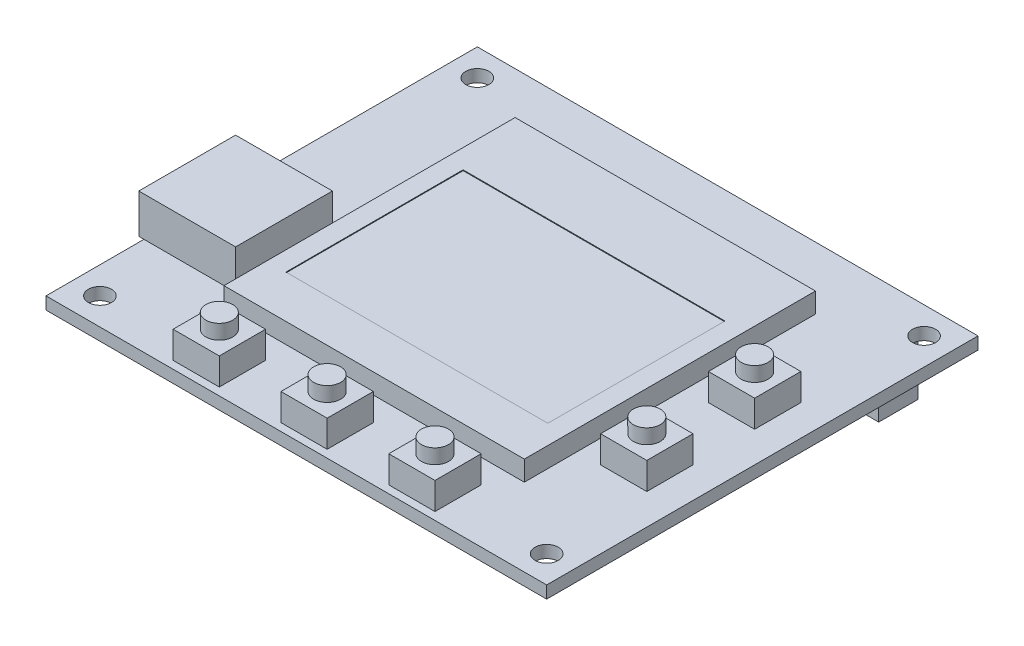
SolidWorks part; units mm, degrees
other "OLED"
other "PCB"
ref_plane "Front Plane" through (0, 0, 0) normal (0, 0, 1) x (1, 0, 0)
ref_plane "Top Plane" through (0, 0, 0) normal (0, 1, 0) x (1, 0, 0)
ref_plane "Right Plane" through (0, 0, 0) normal (1, 0, 0) x (0, 0, -1)
sketch "Sketch1" plane through (0, 0, 0) normal (0, 1, 0) x (1, 0, 0)
  line L1 (-32.5, -28) -> (32.5, -28)
  line L2 (-32.5, -28) -> (-32.5, 28)
  line L3 (-32.5, 28) -> (32.5, 28)
  line L4 (32.5, -28) -> (32.5, 28)
  line L5 (0, 28) -> (0, -28) construction
  line L6 (-32.5, 0) -> (32.5, 0) construction
  line L7 (-29, -24.5) -> (29, -24.5) construction
  line L8 (-29, -24.5) -> (-29, 24.5) construction
  line L9 (-29, 24.5) -> (29, 24.5) construction
  line L10 (29, -24.5) -> (29, 24.5) construction
  line L11 (0, 24.5) -> (0, -24.5) construction
  line L12 (-29, 0) -> (29, 0) construction
  circle A0 centre (-29, 24.5) radius 1.5
  circle A1 centre (29, 24.5) radius 1.5
  circle A2 centre (29, -24.5) radius 1.5
  circle A3 centre (-29, -24.5) radius 1.5
  point P0 (0, 0)
  point P4 (0, 0)
  dimension "D5" = 3
  dimension "D1" = 65
  dimension "D2" = 56
  dimension "D3" = 49
  dimension "D4" = 58
extrude "Boss-Extrude1" add sketch "Sketch1" along normal blind 1.6
sketch "Sketch2" plane through (0, 1.6, 0) normal (0, 1, 0) x (1, 0, 0)
  line L0 (-32.5, -28) -> (-32.5, 28) construction
  line L1 (-19.5, -17.9) -> (19.5, -17.9)
  line L2 (-19.5, -17.9) -> (-19.5, 19.9)
  line L3 (-19.5, 19.9) -> (19.5, 19.9)
  line L4 (19.5, -17.9) -> (19.5, 19.9)
  line L5 (0, 19.9) -> (0, -17.9) construction
  line L6 (-19.5, 1) -> (19.5, 1) construction
  line L7 (-32.5, -28) -> (32.5, -28) construction
  point P0 (0, 1)
  dimension "D1" = 32.5
  dimension "D2" = 39
  dimension "D3" = 37.8
  dimension "D4" = 29
  dimension "D5" = 10.1
extrude "Boss-Extrude2" add sketch "Sketch2" along normal blind 2.6 separate body
sketch "Sketch3" plane through (0, 4.2, 0) normal (0, 1, 0) x (1, 0, 0)
  line L0 (0, 19.9) -> (0, -17.9) construction
  line L1 (-17, 10.65) -> (17, 10.65)
  line L2 (-17, 10.65) -> (-17, -12.35)
  line L3 (-17, -12.35) -> (17, -12.35)
  line L4 (17, 10.65) -> (17, -12.35)
  line L5 (0, -12.35) -> (0, 10.65) construction
  line L6 (-17, -0.85) -> (17, -0.85) construction
  line L7 (-19.5, 19.9) -> (19.5, 19.9) construction
  point P0 (0, -0.85)
  point P4 (0, 0)
  dimension "D1" = 23
  dimension "D2" = 20.75
  dimension "D3" = 34
extrude "Cut-Extrude1" cut sketch "Sketch3" against normal blind 0.1
sketch "Sketch4" plane through (0, 1.6, 0) normal (0, 1, 0) x (1, 0, 0)
  line L0 (-32.5, -28) -> (32.5, -28) construction
  line L1 (-33.17, -2.715) -> (-20.6, -2.715)
  line L2 (-33.17, -2.715) -> (-33.17, -15.285)
  line L3 (-33.17, -15.285) -> (-20.6, -15.285)
  line L4 (-20.6, -2.715) -> (-20.6, -15.285)
  line L5 (-26.885, -15.285) -> (-26.885, -2.715) construction
  line L6 (-33.17, -9) -> (-20.6, -9) construction
  line L7 (-32.5, -28) -> (-32.5, 28) construction
  point P0 (-26.885, -9)
  dimension "D1" = 19
  dimension "D2" = 11.9
  dimension "D3" = 12.57
  dimension "D4" = 12.57
extrude "Boss-Extrude3" add sketch "Sketch4" along normal blind 5.1 separate body
sketch "Sketch5" plane through (0, 1.6, 0) normal (0, 1, 0) x (1, 0, 0)
  line L0 (0, 19.9) -> (0, -17.9) construction
  line L1 (-3, -27) -> (3, -27)
  line L2 (-3, -27) -> (-3, -21)
  line L3 (-3, -21) -> (3, -21)
  line L4 (3, -27) -> (3, -21)
  line L5 (0, -21) -> (0, -27) construction
  line L6 (-3, -24) -> (3, -24) construction
  line L7 (-32.5, -28) -> (32.5, -28) construction
  line L8 (0, 28) -> (0, -28) construction
  line L9 (0, 28) -> (0, -28) construction
  line L10 (-32.5, -28) -> (-32.5, 28) construction
  line L11 (11, -27) -> (17, -27)
  line L12 (11, -27) -> (11, -21)
  line L13 (11, -21) -> (17, -21)
  line L14 (17, -27) -> (17, -21)
  line L15 (14, -21) -> (14, -27) construction
  line L16 (11, -24) -> (17, -24) construction
  line L17 (-11, -21) -> (-3, -21) construction
  line L18 (-17, -27) -> (-11, -27)
  line L19 (-17, -27) -> (-17, -21)
  line L20 (-17, -21) -> (-11, -21)
  line L21 (-11, -27) -> (-11, -21)
  line L22 (-14, -21) -> (-14, -27) construction
  line L23 (-17, -24) -> (-11, -24) construction
  line L24 (3, -21) -> (11, -21) construction
  line L26 (22.5, 3) -> (28.5, 3)
  line L27 (22.5, 3) -> (22.5, 9)
  line L28 (22.5, 9) -> (28.5, 9)
  line L29 (28.5, 3) -> (28.5, 9)
  line L30 (25.5, 9) -> (25.5, 3) construction
  line L31 (22.5, 6) -> (28.5, 6) construction
  line L32 (22.5, -11) -> (28.5, -11)
  line L33 (22.5, -11) -> (22.5, -5)
  line L34 (22.5, -5) -> (28.5, -5)
  line L35 (28.5, -11) -> (28.5, -5)
  line L36 (25.5, -5) -> (25.5, -11) construction
  line L37 (22.5, -8) -> (28.5, -8) construction
  point P0 (0, -24)
  point P10 (14, -24)
  point P14 (25.5, 6)
  point P17 (-14, -24)
  point P24 (25.5, -8)
  point P28 (0, 0)
  dimension "D1" = 6
  dimension "D2" = 6
  dimension "D3" = 4
  dimension "D4" = 46.5
  dimension "D5" = 20
  dimension "D6" = 58
  dimension "D7" = 34
extrude "Boss-Extrude4" add sketch "Sketch5" along normal blind 3.5 separate body
sketch "Sketch6" plane through (0, 5.1, 0) normal (0, 1, 0) x (1, 0, 0)
  circle A0 centre (-14, -24) radius 1.75
  circle A1 centre (0, -24) radius 1.75
  circle A2 centre (14, -24) radius 1.75
  circle A3 centre (25.5, -8) radius 1.75
  circle A4 centre (25.5, 6) radius 1.75
  point P10 (0, 0)
  point P12 (0, 0)
  point P15 (0, 0)
  point P16 (0, 0)
  point P18 (0, 0)
  dimension "D1" = 3.5
extrude "Boss-Extrude5" add sketch "Sketch6" along normal offset from surface (1.9 mm away) 7 up to face at (29, 0, 26)
sketch "Sketch7" plane through (0, 0, 0) normal (0, -1, 0) x (1, 0, 0)
  line L0 (0, -28) -> (0, 28) construction
  line L1 (25.65, -21.96) -> (-25.65, -21.96)
  line L2 (25.65, -21.96) -> (25.65, -27.04)
  line L3 (25.65, -27.04) -> (-25.65, -27.04)
  line L4 (-25.65, -21.96) -> (-25.65, -27.04)
  line L5 (0, -27.04) -> (0, -21.96) construction
  line L6 (25.65, -24.5) -> (-25.65, -24.5) construction
  line L7 (-29, -24.5) -> (29, -24.5) construction
  point P0 (0, -24.5)
  point P4 (0, 0)
  point P7 (0, 0)
  dimension "D1" = 5.08
  dimension "D2" = 51.3
extrude "Boss-Extrude6" add sketch "Sketch7" along normal blind 8.5 separate body
